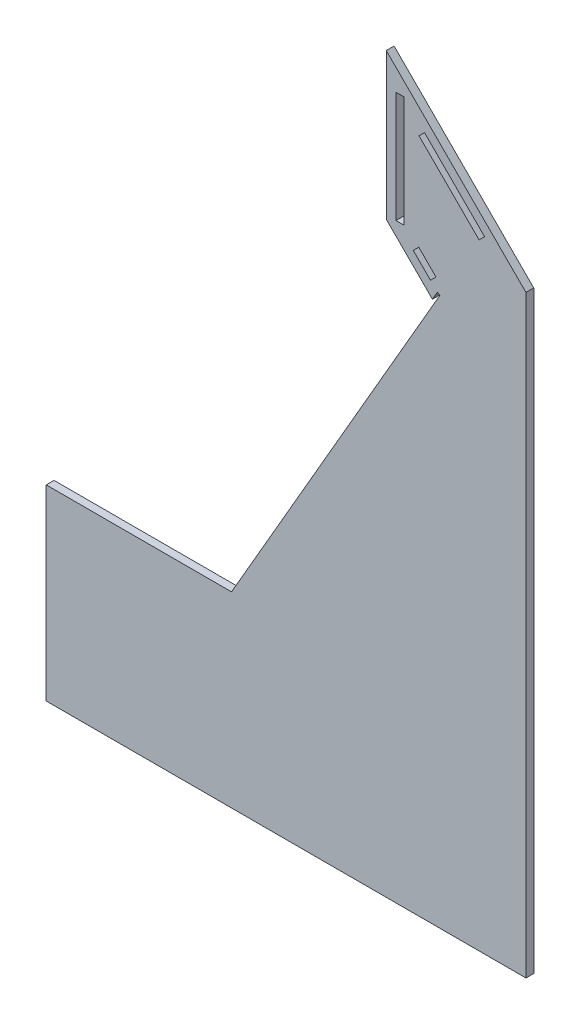
SolidWorks part; units mm, degrees
ref_plane "Front Plane" through (0, 0, 0) normal (0, 0, 1) x (1, 0, 0)
ref_plane "Top Plane" through (0, 0, 0) normal (0, 1, 0) x (1, 0, 0)
ref_plane "Right Plane" through (0, 0, 0) normal (1, 0, 0) x (0, 0, -1)
sketch "Sketch1" plane through (0, 0, 0) normal (0, 0, 1) x (1, 0, 0)
  line L0 (0, 192) -> (190, 192) construction
  line L1 (0, 0) -> (492, 0)
  line L2 (0, 0) -> (0, 192)
  line L3 (0, 192) -> (190, 192)
  line L5 (190, 192) -> (398.25, 552.6996)
  line L6 (398.25, 552.6996) -> (348.7525, 602.1971)
  line L7 (348.7525, 602.1971) -> (348.7525, 752.1971)
  line L8 (348.7525, 752.1971) -> (492, 608.9496)
  line L9 (492, 608.9496) -> (492, 0)
  line L13 (398.25, 552.6996) -> (403.7528, 562.2307)
  line L14 (403.7528, 562.2307) -> (401.1547, 563.7307)
  line L15 (401.1547, 563.7307) -> (396.0538, 554.8957)
  line L16 (191.1547, 200) -> (401.1547, 563.7307) construction
  line L17 (376.406, 588.4794) -> (394.0836, 570.8017) construction
  line L18 (394.0836, 570.8017) -> (399.7405, 576.4586) construction
  line L19 (399.7405, 576.4586) -> (382.0628, 594.1363) construction
  line L20 (382.0628, 594.1363) -> (376.406, 588.4794) construction
  line L29 (366.7283, 606.1571) -> (366.7283, 720.0871) construction
  line L30 (366.7283, 720.0871) -> (358.7283, 720.0871) construction
  line L31 (358.7283, 720.0871) -> (358.7283, 606.1571) construction
  line L32 (358.7283, 606.1571) -> (366.7283, 606.1571) construction
  line L33 (382.2846, 693.217) -> (443.9161, 631.5856) construction
  line L34 (443.9161, 631.5856) -> (449.5729, 637.2424) construction
  line L35 (449.5729, 637.2424) -> (387.9415, 698.8739) construction
  line L36 (387.9415, 698.8739) -> (382.2846, 693.217) construction
  line L37 (376.406, 588.4794) -> (394.0836, 570.8017)
  line L38 (394.0836, 570.8017) -> (399.7405, 576.4586)
  line L39 (399.7405, 576.4586) -> (382.0628, 594.1363)
  line L40 (382.0628, 594.1363) -> (376.406, 588.4794)
  line L41 (366.7283, 606.1571) -> (366.7283, 720.0871)
  line L42 (366.7283, 720.0871) -> (358.7283, 720.0871)
  line L43 (358.7283, 720.0871) -> (358.7283, 606.1571)
  line L44 (358.7283, 606.1571) -> (366.7283, 606.1571)
  line L45 (382.2846, 693.217) -> (443.9161, 631.5856)
  line L46 (443.9161, 631.5856) -> (449.5729, 637.2424)
  line L47 (449.5729, 637.2424) -> (387.9415, 698.8739)
  line L48 (387.9415, 698.8739) -> (382.2846, 693.217)
  dimension "D3" = 60
  dimension "D1" = 492
  dimension "D2" = 192
  dimension "D4" = 416.5
  dimension "D5" = 190
  dimension "D6" = 150
  dimension "D7" = 70
  dimension "D8" = 105
extrude "Boss-Extrude1" add sketch "Sketch1" along normal blind 8
